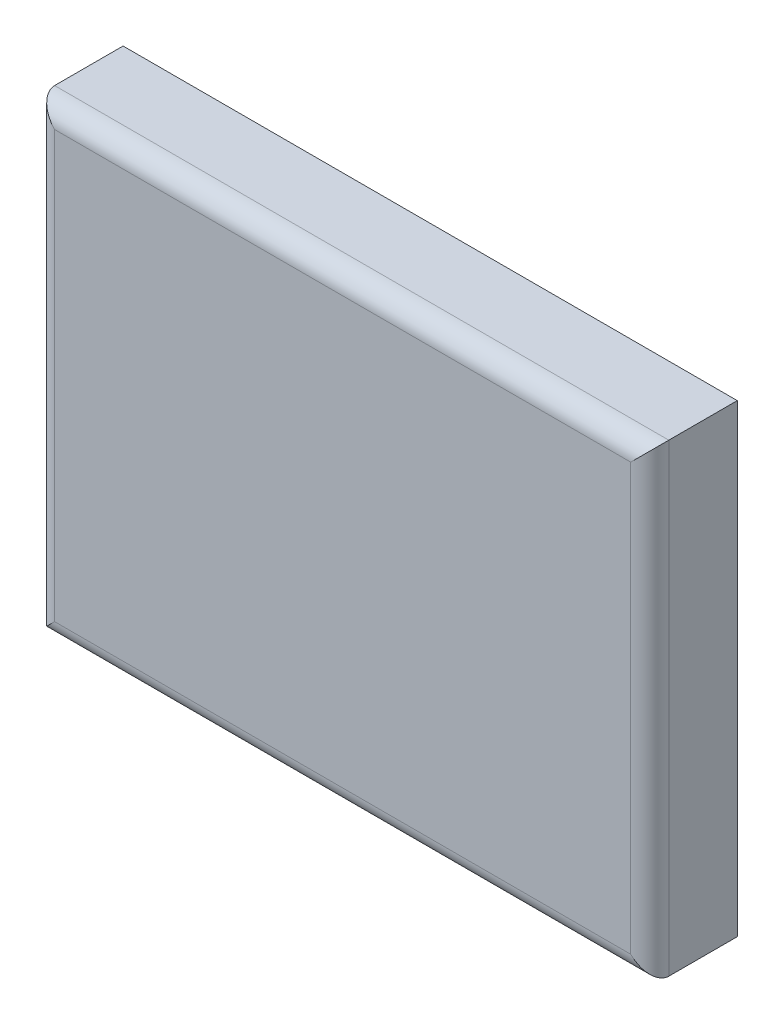
SolidWorks part; units mm, degrees
ref_plane "Спереди" through (0, 0, 0) normal (0, 0, 1) x (1, 0, 0)
ref_plane "Сверху" through (0, 0, 0) normal (0, 1, 0) x (1, 0, 0)
ref_plane "Справа" through (0, 0, 0) normal (1, 0, 0) x (0, 0, -1)
sketch "Эскиз1" plane through (0, 0, 0) normal (0, 0, 1) x (1, 0, 0)
  line L1 (-8.07, -6.1) -> (8.07, -6.1)
  line L2 (-8.07, -6.1) -> (-8.07, 6.1)
  line L3 (-8.07, 6.1) -> (8.07, 6.1)
  line L4 (8.07, -6.1) -> (8.07, 6.1)
  line L5 (-8.07, -6.1) -> (8.07, 6.1) construction
  line L6 (-8.07, 6.1) -> (8.07, -6.1) construction
  point P0 (0, 0)
  dimension "D1" = 16.14
  dimension "D2" = 12.2
extrude "Бобышка-Вытянуть1" add sketch "Эскиз1" along normal blind 2.3
fillet "Скругление1" radius 0.5 4 edges at (0, -6.1, 2.3) (-8.07, 0, 2.3) (0, 6.1, 2.3) (8.07, 0, 2.3)
